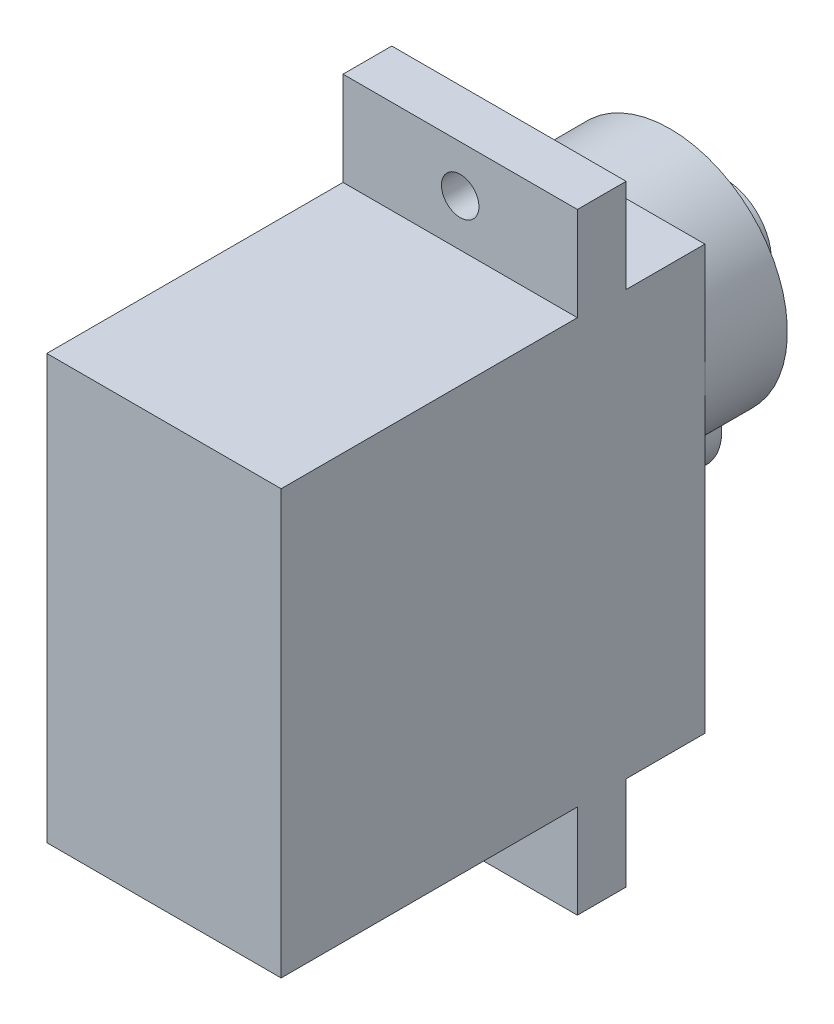
SolidWorks part; units mm, degrees
ref_plane "Front Plane" through (0, 0, 0) normal (0, 0, 1) x (1, 0, 0)
ref_plane "Top Plane" through (0, 0, 0) normal (0, 1, 0) x (1, 0, 0)
ref_plane "Right Plane" through (0, 0, 0) normal (1, 0, 0) x (0, 0, -1)
sketch "Sketch1" plane through (0, 0, 0) normal (1, 0, 0) x (0, 0, -1)
  line L0 (0, 0) -> (0, 5)
  line L1 (0, 5) -> (-15.8, 5)
  line L2 (-15.8, 5) -> (-15.8, 27.6)
  line L3 (-15.8, 27.6) -> (0, 27.6)
  line L4 (0, 27.6) -> (0, 32.6)
  line L5 (0, 32.6) -> (2.6, 32.6)
  line L6 (2.6, 32.6) -> (2.6, 27.6)
  line L7 (2.6, 27.6) -> (6.8, 27.6)
  line L8 (6.8, 27.6) -> (6.8, 5)
  line L9 (6.8, 5) -> (2.6, 5)
  line L10 (2.6, 5) -> (2.6, 0)
  line L11 (2.6, 0) -> (0, 0)
  dimension "D1" = 22.6
  dimension "D2" = 15.8
  dimension "D3" = 5
  dimension "D4" = 2.6
  dimension "D5" = 4.2
extrude "Boss-Extrude1" add sketch "Sketch1" along normal blind 12.5
sketch "Sketch2" plane through (0, 0, -6.8) normal (0, 0, -1) x (-1, 0, 0)
  line L1 (-12.5, 27.6) -> (0, 27.6) construction
  line L2 (0, 5) -> (0, 27.6) construction
  line L3 (-12.5, 5) -> (0, 5) construction
  arc A0 (-8.9108, 15.6947) -> (-3.5892, 15.6947) centre (-6.25, 21.35) cw
  arc A1 (-8.9108, 15.6947) -> (-3.5892, 15.6947) centre (-6.25, 15) ccw
  point P6 (-6.25, 27.6)
  dimension "D1" = 2.75
  dimension "D2" = 10
extrude "Boss-Extrude2" add sketch "Sketch2" along normal blind 4.4
sketch "Sketch3" plane through (0, 0, -11.2) normal (0, 0, -1) x (-1, 0, 0)
  circle A0 centre (-6.25, 21.35) radius 2.5
  arc A1 (-3.5892, 15.6947) -> (-8.9108, 15.6947) centre (-6.25, 21.35) ccw construction
  dimension "D1" = 5
extrude "Boss-Extrude3" add sketch "Sketch3" along normal blind 2.9
sketch "Sketch4" plane through (0, 0, -2.6) normal (0, 0, -1) x (-1, 0, 0)
  line L0 (-12.5, 27.6) -> (0, 27.6) construction
  line L1 (-12.5, 5) -> (0, 5) construction
  line L2 (-12.5, 32.6) -> (0, 32.6) construction
  circle A0 centre (-6.25, 30.1) radius 1
  circle A1 centre (-6.25, 2.5) radius 1
  point P10 (-6.25, 32.6)
  dimension "D3" = 2
  dimension "D1" = 2.5
  dimension "D2" = 2.5
extrude "Cut-Extrude1" cut sketch "Sketch4" against normal through all
